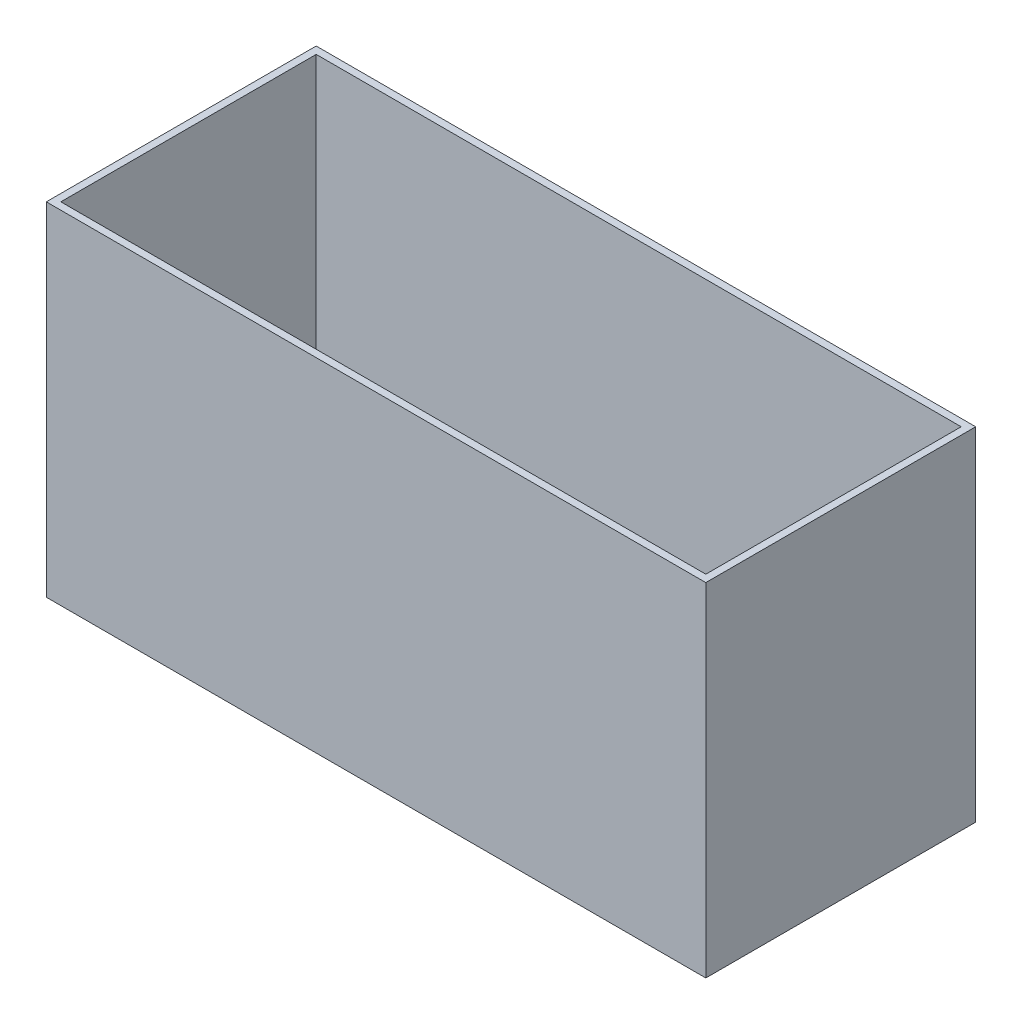
SolidWorks part; units mm, degrees
ref_plane "Front Plane" through (0, 0, 0) normal (0, 0, 1) x (1, 0, 0)
ref_plane "Top Plane" through (0, 0, 0) normal (0, 1, 0) x (1, 0, 0)
ref_plane "Right Plane" through (0, 0, 0) normal (1, 0, 0) x (0, 0, -1)
sketch "Sketch1" plane through (0, 0, 0) normal (0, 1, 0) x (1, 0, 0)
  line L1 (-454.5, -186) -> (454.5, -186)
  line L2 (-454.5, -186) -> (-454.5, 186)
  line L3 (-454.5, 186) -> (454.5, 186)
  line L4 (454.5, -186) -> (454.5, 186)
  line L5 (-454.5, -186) -> (454.5, 186) construction
  line L6 (-454.5, 186) -> (454.5, -186) construction
  point P0 (0, 0)
extrude "Bottom Plate" add sketch "Sketch1" along normal blind 10
sketch "Sketch2" plane through (0, 0, 0) normal (0, 1, 0) x (1, 0, 0)
  line L1 (-454.5, 176) -> (454.5, 176)
  line L2 (-454.5, 176) -> (-454.5, 186)
  line L3 (-454.5, 186) -> (454.5, 186)
  line L4 (454.5, 176) -> (454.5, 186)
  line L5 (-454.5, 176) -> (454.5, 186) construction
  line L6 (-454.5, 186) -> (454.5, 176) construction
  point P0 (0, 181)
extrude "Left Wall" add sketch "Sketch2" along normal blind 472
sketch "Sketch3" plane through (0, 0, 0) normal (0, 1, 0) x (1, 0, 0)
  line L0 (454.5, -186) -> (454.5, 176) construction
  line L1 (-454.5, -186) -> (454.5, -186)
  line L2 (-454.5, -186) -> (-454.5, -176)
  line L3 (-454.5, -176) -> (454.5, -176)
  line L4 (454.5, -186) -> (454.5, -176)
  line L5 (-454.5, -186) -> (454.5, -176) construction
  line L6 (-454.5, -176) -> (454.5, -186) construction
  point P0 (0, -181)
extrude "Right Wall" add sketch "Sketch3" along normal blind 472
sketch "Sketch4" plane through (0, 0, 0) normal (0, 1, 0) x (1, 0, 0)
  line L1 (444.5, -176) -> (454.5, -176)
  line L2 (444.5, -176) -> (444.5, 176)
  line L3 (444.5, 176) -> (454.5, 176)
  line L4 (454.5, -176) -> (454.5, 176)
  line L5 (444.5, -176) -> (454.5, 176) construction
  line L6 (444.5, 176) -> (454.5, -176) construction
  point P0 (449.5, 0)
extrude "Back Wall" add sketch "Sketch4" along normal blind 472
sketch "Sketch5" plane through (0, 0, 0) normal (0, 1, 0) x (1, 0, 0)
  line L0 (-454.5, 176) -> (444.5, 176) construction
  line L1 (-454.5, -176) -> (-444.5, -176)
  line L2 (-454.5, -176) -> (-454.5, 176)
  line L3 (-454.5, 176) -> (-444.5, 176)
  line L4 (-444.5, -176) -> (-444.5, 176)
  line L5 (-454.5, -176) -> (-444.5, 176) construction
  line L6 (-454.5, 176) -> (-444.5, -176) construction
  point P0 (-449.5, 0)
extrude "Front Wall" add sketch "Sketch5" along normal blind 472
